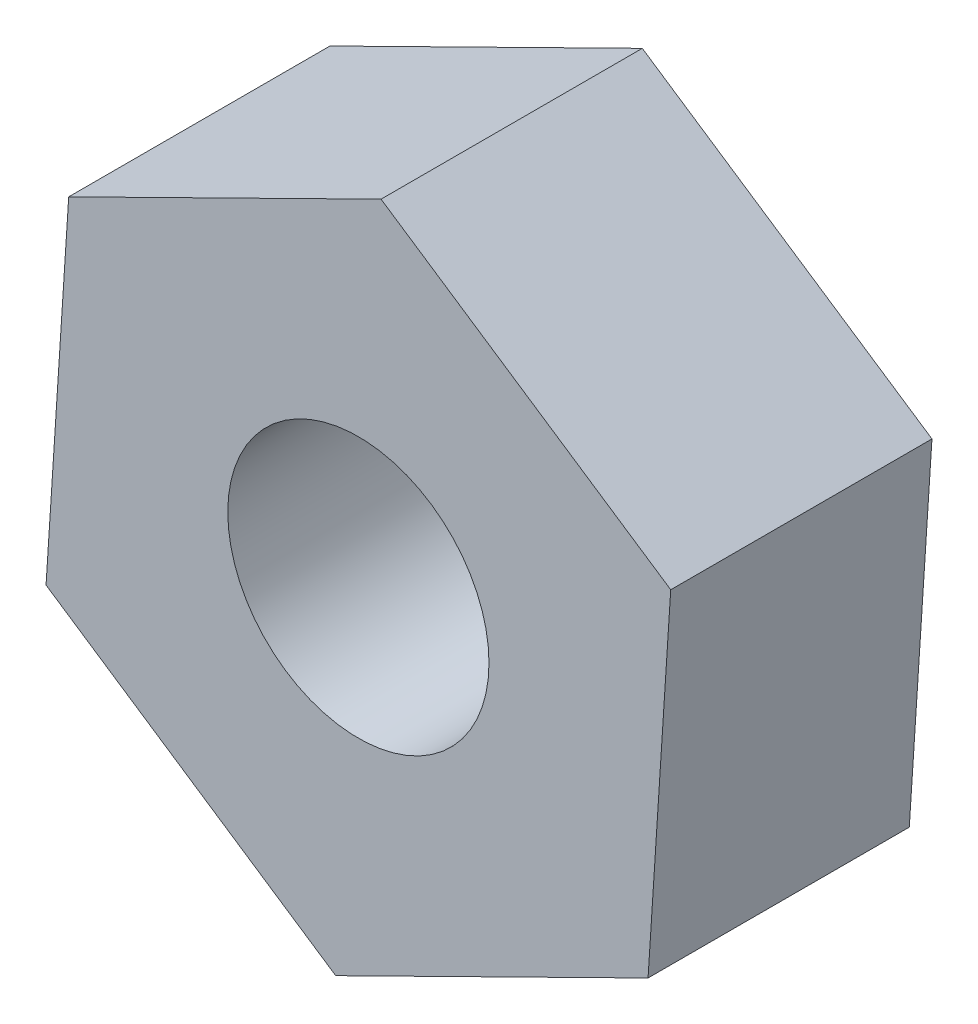
SolidWorks part; units mm, degrees
ref_plane "Front Plane" through (0, 0, 0) normal (0, 0, 1) x (1, 0, 0)
ref_plane "Top Plane" through (0, 0, 0) normal (0, 1, 0) x (1, 0, 0)
ref_plane "Right Plane" through (0, 0, 0) normal (1, 0, 0) x (0, 0, -1)
sketch "Sketch1" plane through (0, 0, 0) normal (0, 0, 1) x (1, 0, 0)
  line L1 (3.3266, -2.2213) -> (3.587, 1.7703)
  line L2 (3.587, 1.7703) -> (0.2604, 3.9915)
  line L3 (0.2604, 3.9915) -> (-3.3266, 2.2213)
  line L4 (-3.3266, 2.2213) -> (-3.587, -1.7703)
  line L5 (-3.587, -1.7703) -> (-0.2604, -3.9915)
  line L6 (-0.2604, -3.9915) -> (3.3266, -2.2213)
  circle A0 centre (0, 0) radius 3.4641 construction
  dimension "D1" = 4
extrude "Boss-Extrude1" add sketch "Sketch1" along normal blind 3
sketch "Sketch2" plane through (0, 0, 3) normal (0, 0, 1) x (1, 0, 0)
  circle A0 centre (0, 0) radius 1.5
  dimension "D1" = 3
extrude "Cut-Extrude1" cut sketch "Sketch2" against normal through all
